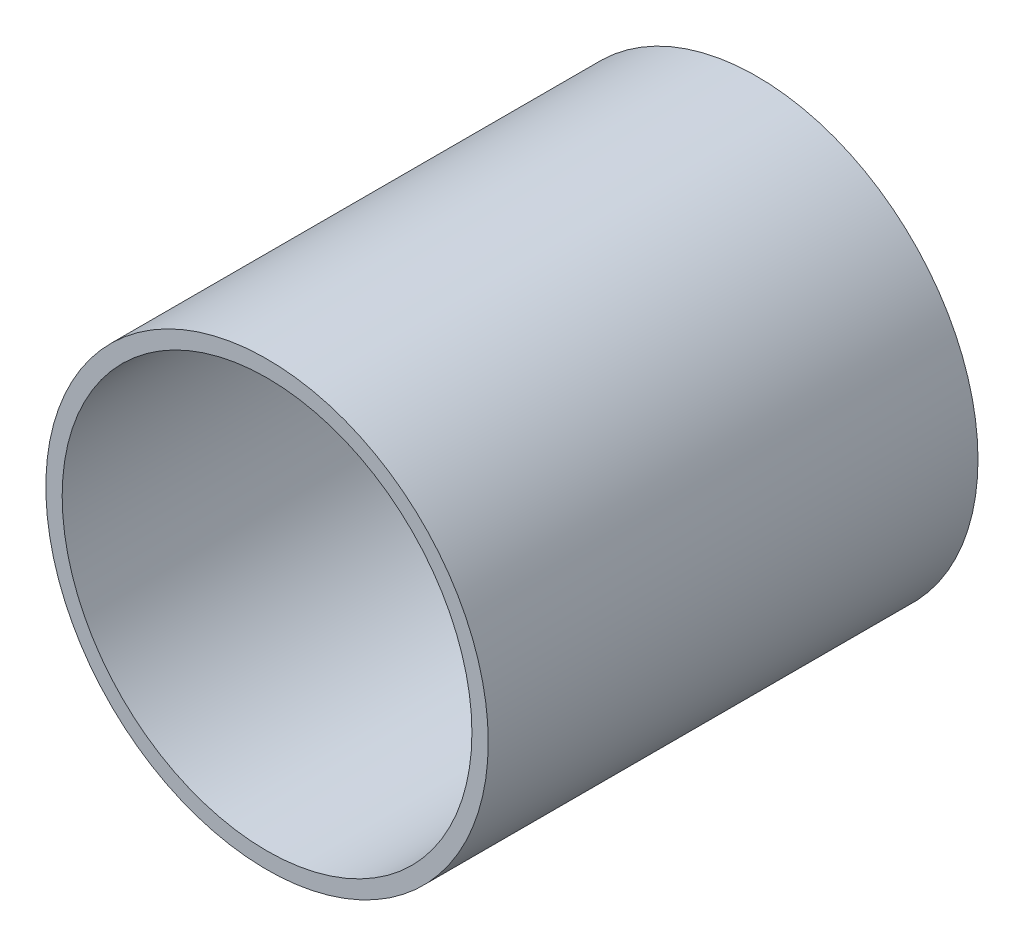
SolidWorks part; units mm, degrees
material "Латунь"
ref_plane "Спереди" through (0, 0, 0) normal (0, 0, 1) x (1, 0, 0)
ref_plane "Сверху" through (0, 0, 0) normal (0, 1, 0) x (1, 0, 0)
ref_plane "Справа" through (0, 0, 0) normal (1, 0, 0) x (0, 0, -1)
other "Configuration Table"
sketch "Эскиз1" plane through (0, 0, 0) normal (0, 0, 1) x (1, 0, 0)
  circle A0 centre (0, 0) radius 12.55
  circle A2 centre (0, 0) radius 13.55
  dimension "D1" = 25.1
  dimension "D2" = 1
extrude "Бобышка-Вытянуть1" add sketch "Эскиз1" along normal blind 30
